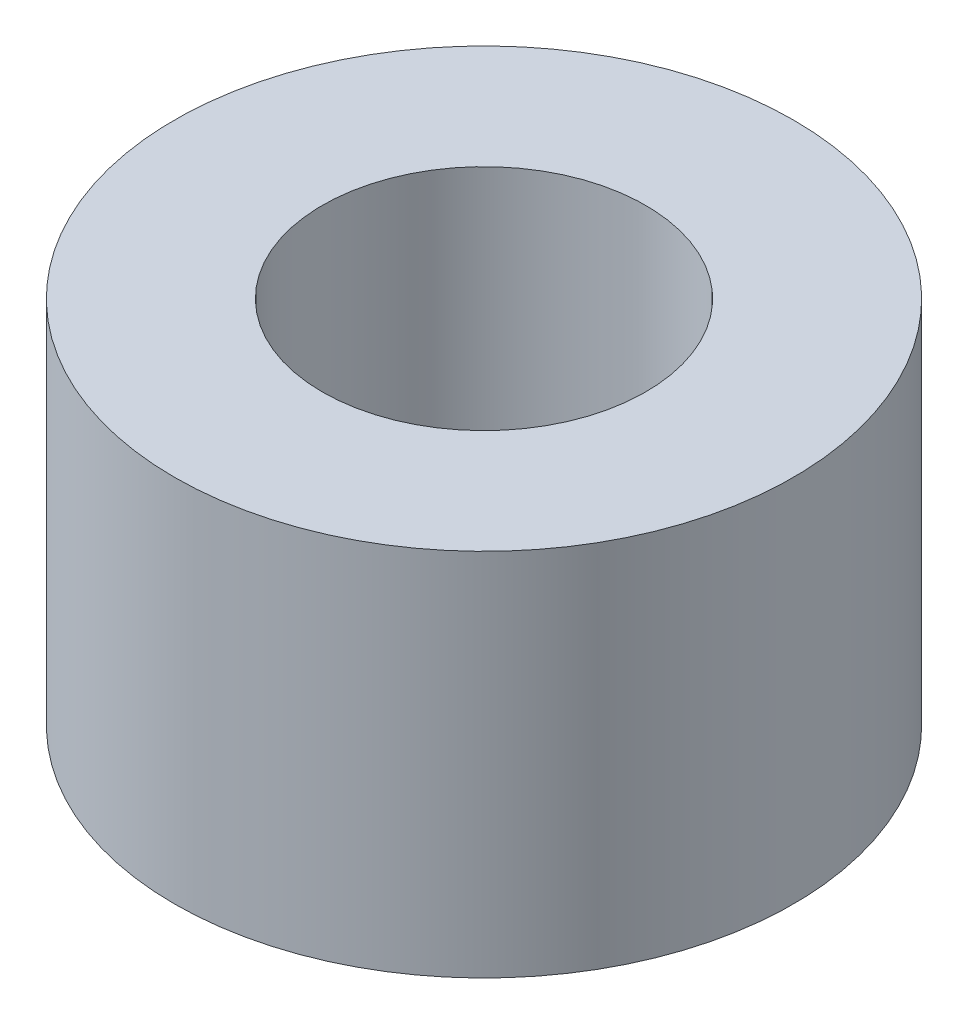
SolidWorks part; units mm, degrees
ref_plane "Front Plane" through (0, 0, 0) normal (0, 0, 1) x (1, 0, 0)
ref_plane "Top Plane" through (0, 0, 0) normal (0, 1, 0) x (1, 0, 0)
ref_plane "Right Plane" through (0, 0, 0) normal (1, 0, 0) x (0, 0, -1)
sketch "Sketch1" plane through (0, 0, 0) normal (0, 1, 0) x (1, 0, 0)
  circle A0 centre (0, 0) radius 1.75
  circle A1 centre (0, 0) radius 3.35
  dimension "D1" = 3.5
  dimension "D2" = 6.7
extrude "Boss-Extrude1" add sketch "Sketch1" along normal blind 4
